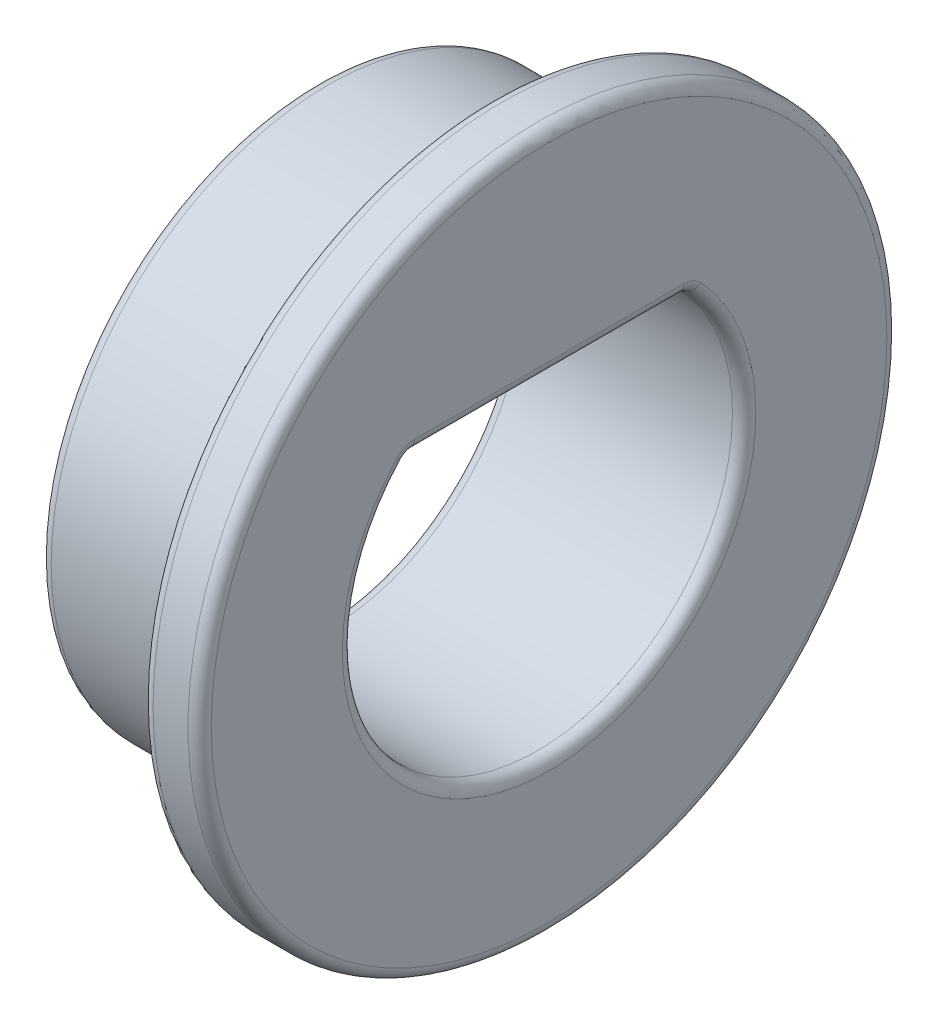
SolidWorks part; units mm, degrees
ref_plane "Front Plane" through (0, 0, 0) normal (0, 0, 1) x (1, 0, 0)
ref_plane "Top Plane" through (0, 0, 0) normal (0, 1, 0) x (1, 0, 0)
ref_plane "Right Plane" through (0, 0, 0) normal (1, 0, 0) x (0, 0, -1)
sketch "Sketch1" plane through (0, 0, 0) normal (0, 0, 1) x (1, 0, 0)
  line L0 (0, 0) -> (-8.0549, 0) construction
  line L1 (-4, 0) -> (-4, 4.75)
  line L2 (-4, 4.75) -> (-1, 4.75)
  line L3 (-1, 4.75) -> (-1, 6)
  line L4 (-1, 6) -> (0, 6)
  line L5 (0, 6) -> (0, 0)
  line L6 (0, 0) -> (-4, 0)
  point P6 (-2.1099, 3.4809)
  point P9 (-8.0549, 0)
  dimension "D1" = 12
  dimension "D2" = 1
  dimension "D3" = 3
  dimension "D4" = 9.5
revolve "Revolve1" add sketch "Sketch1" angle 360 about L0
sketch "Sketch2" plane through (0, 0, 0) normal (1, 0, 0) x (0, 0, -1)
  line L0 (-2.4, 2.3372) -> (2.4, 2.3372)
  arc A0 (2.4, 2.3372) -> (-2.4, 2.3372) centre (0, 0) cw
  point P5 (0, 0)
  dimension "D1" = 3.35
  dimension "D2" = 4.8
extrude "Cut-Extrude1" cut sketch "Sketch2" against normal up to next
fillet "Fillet1" radius 0.2 10 edges at (-4, -3.35, 0) (0, -3.35, 0) (-4, 2.3372, 0) (-2, 2.3372, 2.4) (-2, 2.3372, -2.4) (0, 2.3372, 0) (0, 0, -6) (-1, 0, -6) (-1, 0, -4.75) (-4, 0, -4.75)
